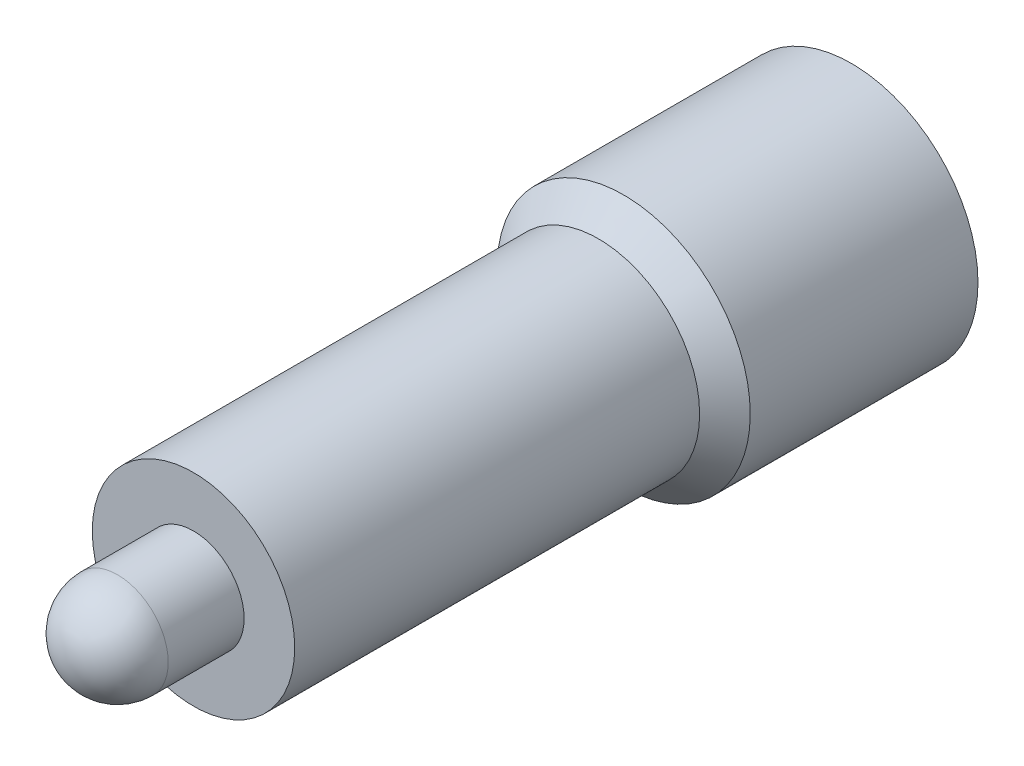
SolidWorks part; units mm, degrees
ref_plane "Спереди" through (0, 0, 0) normal (0, 0, 1) x (1, 0, 0)
ref_plane "Сверху" through (0, 0, 0) normal (0, 1, 0) x (1, 0, 0)
ref_plane "Справа" through (0, 0, 0) normal (1, 0, 0) x (0, 0, -1)
sketch "Эскиз1" plane through (0, 0, 0) normal (0, 0, 1) x (1, 0, 0)
  circle A0 centre (0, 0) radius 5
extrude "Бобышка-Вытянуть1" add sketch "Эскиз1" along normal blind 10
chamfer "Фаска1" distance 1 angle 45 1 edges at (5, 0, 10)
sketch "Эскиз2" plane through (0, 0, 10) normal (0, 0, 1) x (1, 0, 0)
  circle A0 centre (0, 0) radius 4
extrude "Бобышка-Вытянуть2" add sketch "Эскиз2" along normal blind 16
sketch "Эскиз3" plane through (0, 0, 26) normal (0, 0, 1) x (1, 0, 0)
  circle A0 centre (0, 0) radius 2
extrude "Бобышка-Вытянуть3" add sketch "Эскиз3" along normal blind 5
fillet "Скругление1" radius 2 1 edges at (2, 0, 31)
